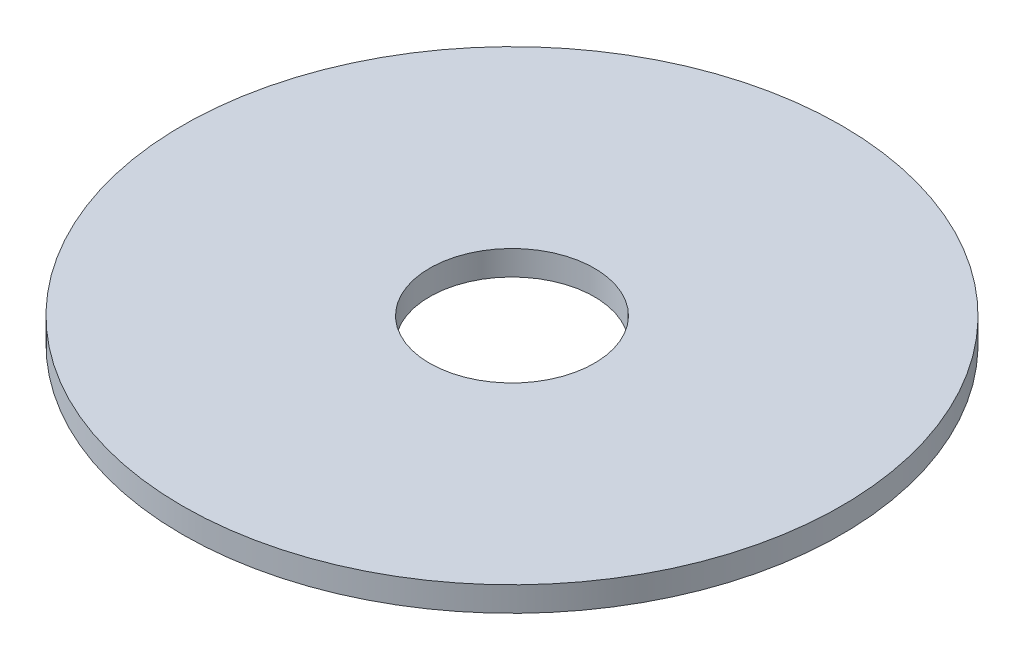
SolidWorks part; units mm, degrees
ref_plane "Front Plane" through (0, 0, 0) normal (0, 0, 1) x (1, 0, 0)
ref_plane "Top Plane" through (0, 0, 0) normal (0, 1, 0) x (1, 0, 0)
ref_plane "Right Plane" through (0, 0, 0) normal (1, 0, 0) x (0, 0, -1)
sketch "Sketch1" plane through (0, 0, 0) normal (0, 1, 0) x (1, 0, 0)
  circle A0 centre (0, 0) radius 20
  dimension "D1" = 40
extrude "Boss-Extrude1" add sketch "Sketch1" along normal blind 1.5
sketch "Sketch2" plane through (0, 1.5, 0) normal (0, 1, 0) x (1, 0, 0)
  circle A0 centre (0, 0) radius 5
  dimension "D1" = 10
extrude "Cut-Extrude1" cut sketch "Sketch2" against normal blind 1.5
